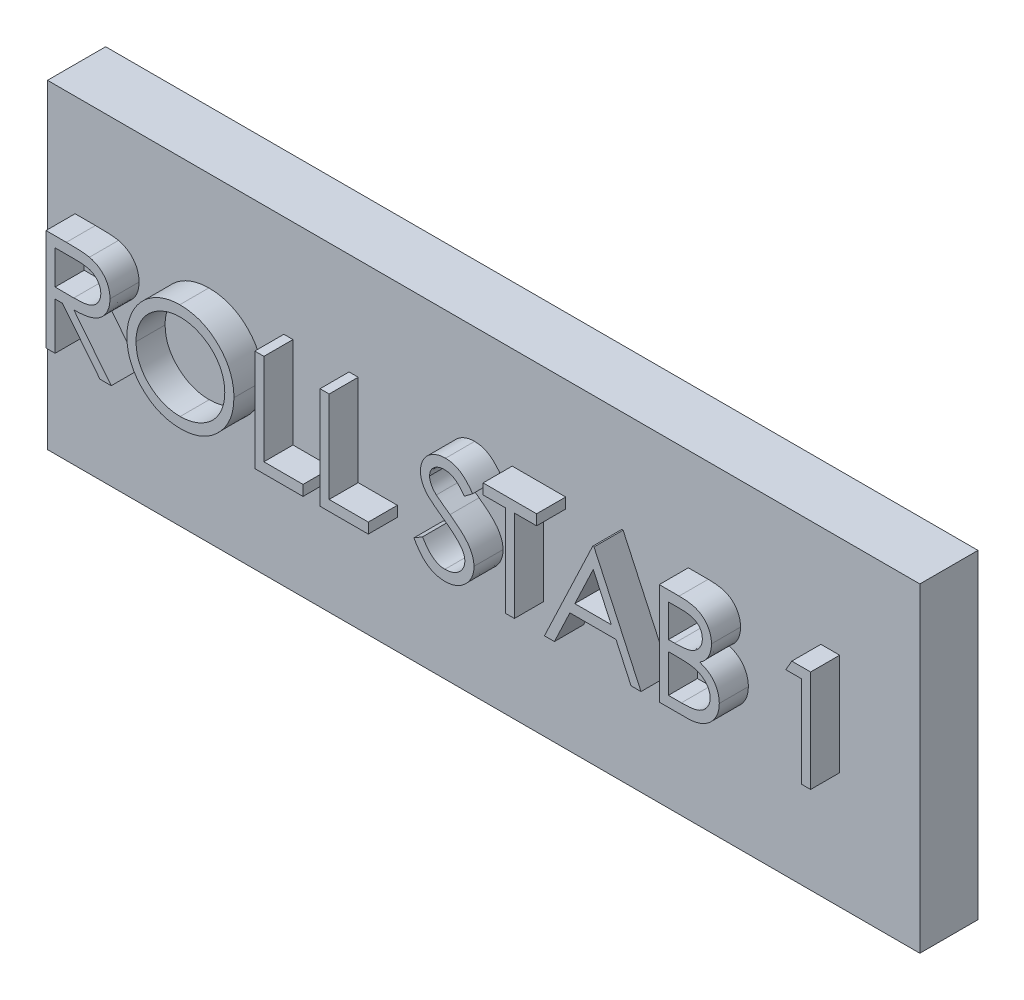
SolidWorks part; units mm, degrees
ref_plane "Front Plane" through (0, 0, 0) normal (0, 0, 1) x (1, 0, 0)
ref_plane "Top Plane" through (0, 0, 0) normal (0, 1, 0) x (1, 0, 0)
ref_plane "Right Plane" through (0, 0, 0) normal (1, 0, 0) x (0, 0, -1)
sketch "Sketch1" plane through (0, 0, 0) normal (0, 0, 1) x (1, 0, 0)
  line L1 (-51.24, 31.58) -> (-21.24, 31.58)
  line L2 (-51.24, 31.58) -> (-51.24, 20.58)
  line L3 (-51.24, 20.58) -> (-21.24, 20.58)
  line L4 (-21.24, 31.58) -> (-21.24, 20.58)
  dimension "D1" = 30
  dimension "D2" = 11
extrude "Boss-Extrude1" add sketch "Sketch1" along normal blind 2
sketch "Sketch3" plane through (0, 0, 2) normal (0, 0, 1) x (1, 0, 0)
  line L0 (-51.24, 31.58) -> (-51.24, 20.58) construction
  line L1 (-21.24, 31.58) -> (-51.24, 31.58) construction
  text T0 "ROLL STAB 1"
  dimension "D1" = 0.5
  dimension "D2" = 7
extrude "Boss-Extrude3" add sketch "Sketch3" along normal blind 1
